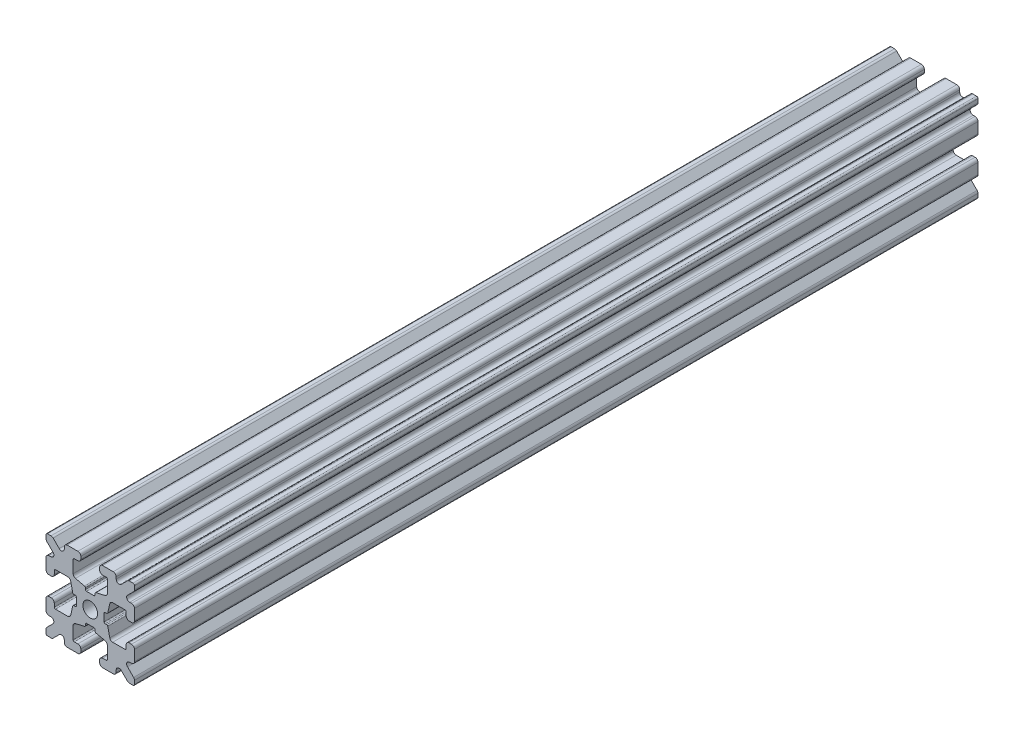
SolidWorks part; units mm, degrees
ref_plane "Front Plane" through (0, 0, 0) normal (0, 0, 1) x (1, 0, 0)
ref_plane "Top Plane" through (0, 0, 0) normal (0, 1, 0) x (1, 0, 0)
ref_plane "Right Plane" through (0, 0, 0) normal (1, 0, 0) x (0, 0, -1)
sketch "Sketch1" plane through (0, 0, 0) normal (0, 0, 1) x (1, 0, 0)
  line L1 (-7.5, -7.5) -> (7.5, -7.5)
  line L2 (-7.5, -7.5) -> (-7.5, 7.5)
  line L3 (-7.5, 7.5) -> (7.5, 7.5)
  line L4 (7.5, -7.5) -> (7.5, 7.5)
  line L5 (-7.5, -7.5) -> (7.5, 7.5) construction
  line L6 (-7.5, 7.5) -> (7.5, -7.5) construction
  circle A0 centre (0, 0) radius 1.25
  point P0 (0, 0)
  dimension "D2" = 2.5
  dimension "D1" = 15
extrude "Boss-Extrude1" add sketch "Sketch1" along normal mid plane 143
fillet "Fillet1" radius 0.25 4 edges at (7.5, -7.5, 0) (-7.5, -7.5, 0) (7.5, 7.5, 0) (-7.5, 7.5, 0)
sketch "Sketch2" plane through (0, 0, 71.5) normal (0, 0, 1) x (1, 0, 0)
  line L0 (-7.5, 7.25) -> (-7.5, -7.25) construction
  line L1 (-7.5, 1.6) -> (-6.1, 1.6)
  line L2 (-7.5, 1.6) -> (-7.5, -1.6)
  line L3 (-7.5, -1.6) -> (-6.1, -1.6)
  line L4 (-6.1, 1.6) -> (-6.1, 2.9)
  line L5 (0, 0) -> (-12.1036, 0) construction
  line L6 (-6.1, -2.9) -> (-3.4, -2.9)
  line L7 (0, 0) -> (-7.25, 7.25) construction
  line L8 (-6.1, 2.9) -> (-3.4, 2.9)
  line L9 (-3.4, -2.9) -> (-3.4, 2.9)
  line L10 (55, 0) -> (-55, 0) construction
  line L11 (-6.1, -2.9) -> (-6.1, -1.6)
  line L12 (2.9, 6.1) -> (1.6, 6.1)
  line L13 (2.9, 3.4) -> (-2.9, 3.4)
  line L14 (-2.9, 6.1) -> (-2.9, 3.4)
  line L15 (2.9, 6.1) -> (2.9, 3.4)
  line L16 (-1.6, 6.1) -> (-2.9, 6.1)
  line L17 (1.6, 7.5) -> (1.6, 6.1)
  line L18 (-1.6, 7.5) -> (1.6, 7.5)
  line L19 (-1.6, 7.5) -> (-1.6, 6.1)
  line L20 (-1.6, -7.5) -> (-1.6, -6.1)
  line L21 (-1.6, -7.5) -> (1.6, -7.5)
  line L22 (1.6, -7.5) -> (1.6, -6.1)
  line L23 (-1.6, -6.1) -> (-2.9, -6.1)
  line L24 (2.9, -6.1) -> (2.9, -3.4)
  line L25 (-2.9, -6.1) -> (-2.9, -3.4)
  line L26 (2.9, -3.4) -> (-2.9, -3.4)
  line L27 (2.9, -6.1) -> (1.6, -6.1)
  line L28 (6.1, -2.9) -> (6.1, -1.6)
  line L29 (3.4, -2.9) -> (3.4, 2.9)
  line L30 (6.1, 2.9) -> (3.4, 2.9)
  line L31 (6.1, -2.9) -> (3.4, -2.9)
  line L32 (6.1, 1.6) -> (6.1, 2.9)
  line L33 (7.5, -1.6) -> (6.1, -1.6)
  line L34 (7.5, 1.6) -> (7.5, -1.6)
  line L35 (7.5, 1.6) -> (6.1, 1.6)
  dimension "D1" = 3.2
  dimension "D2" = 5.8
  dimension "D3" = 1.4
  dimension "D4" = 2.7
extrude "Cut-Extrude1" cut sketch "Sketch2" against normal through all
sketch "Sketch4" plane through (0, 0, 71.5) normal (0, 0, 1) x (1, 0, 0)
  line L0 (-3.4, 2.9) -> (-2.75, 0)
  line L1 (55, 0) -> (-55, 0) construction
  line L2 (-2.75, 0) -> (-3.4, -2.9)
  line L3 (-3.4, -2.9) -> (-3.4, 2.9) construction
  line L4 (-3.4, 2.9) -> (-3.4, -2.9)
  line L5 (-2.9, 3.4) -> (0, 2.75)
  line L6 (0, 2.75) -> (2.9, 3.4)
  line L7 (2.9, 3.4) -> (-2.9, 3.4)
  line L8 (3.4, 2.9) -> (2.75, 0)
  line L9 (2.75, 0) -> (3.4, -2.9)
  line L10 (3.4, -2.9) -> (3.4, 2.9)
  line L11 (-2.9, -3.4) -> (0, -2.75)
  line L12 (0, -2.75) -> (2.9, -3.4)
  line L13 (2.9, -3.4) -> (-2.9, -3.4)
  circle A2 centre (0, 0) radius 2.75
  circle A3 centre (0, 0) radius 2.75 construction
  dimension "D1" = 1.5
extrude "Cut-Extrude3" cut sketch "Sketch4" against normal through all
fillet "Fillet3" radius 0.5 16 edges at (-6.1, -1.6, 0) (-7.5, -1.6, 0) (-6.1, 1.6, 0) (-7.5, 1.6, 0) (-1.6, -7.5, 0) (-1.6, -6.1, 0) (1.6, -7.5, 0) (1.6, -6.1, 0) (6.1, -1.6, 0) (7.5, -1.6, 0) (7.5, 1.6, 0) (6.1, 1.6, 0) (1.6, 7.5, 0) (1.6, 6.1, 0) (-1.6, 7.5, 0) (-1.6, 6.1, 0)
fillet "Fillet4" radius 0.5 8 edges at (-3.4, 2.9, 0) (-3.4, -2.9, 0) (2.9, -3.4, 0) (-2.9, -3.4, 0) (3.4, -2.9, 0) (3.4, 2.9, 0) (-2.9, 3.4, 0) (2.9, 3.4, 0)
fillet "Fillet5" radius 3 4 edges at (0, -2.75, 0) (2.75, 0, 0) (-2.75, 0, 0) (0, 2.75, 0)
fillet "Fillet6" radius 0.2 8 edges at (-2.9, -6.1, 0) (2.9, -6.1, 0) (6.1, -2.9, 0) (6.1, 2.9, 0) (2.9, 6.1, 0) (-2.9, 6.1, 0) (-6.1, -2.9, 0) (-6.1, 2.9, 0)
sketch "Sketch5" plane through (0, 0, 71.5) normal (0, 0, 1) x (1, 0, 0)
  line L0 (0, 0) -> (-7.25, 7.25) construction
  line L1 (-7.5, 6.4393) -> (-5.4607, 4.4)
  line L2 (-6.4393, 7.5) -> (-4.4, 5.4607)
  line L3 (-7.5, 4.4) -> (-5.4607, 4.4)
  line L4 (-3.8003, 2.9) -> (-5.9, 2.9) construction
  line L5 (0, 0) -> (-12.1819, 0) construction
  line L6 (-4.4, 7.5) -> (-4.4, 5.4607)
  line L7 (-2.9, 5.9) -> (-2.9, 3.8003) construction
  line L8 (-7.5, 6.4393) -> (-7.5, 4.4)
  line L9 (-7.5, 7.25) -> (-7.5, 2.1) construction
  line L10 (2.1, -7.5) -> (7.25, -7.5) construction
  line L11 (7.5, -7.25) -> (7.5, -2.1) construction
  line L12 (7.25, 7.5) -> (2.1, 7.5) construction
  line L13 (-2.1, 7.5) -> (-7.25, 7.5) construction
  line L14 (-4.4, 7.5) -> (-6.4393, 7.5)
  line L16 (55, 0) -> (-55, 0) construction
  line L17 (0, 0) -> (0, 10.993) construction
  line L18 (0, -54.6431) -> (0, 54.6431) construction
  line L20 (4.4, 7.5) -> (6.4393, 7.5)
  line L22 (7.5, 6.4393) -> (7.5, 4.4)
  line L23 (4.4, 7.5) -> (4.4, 5.4607)
  line L24 (7.5, 4.4) -> (5.4607, 4.4)
  line L25 (6.4393, 7.5) -> (4.4, 5.4607)
  line L26 (7.5, 6.4393) -> (5.4607, 4.4)
  line L27 (7.5, -6.4393) -> (5.4607, -4.4)
  line L28 (6.4393, -7.5) -> (4.4, -5.4607)
  line L29 (7.5, -4.4) -> (5.4607, -4.4)
  line L30 (4.4, -7.5) -> (4.4, -5.4607)
  line L31 (7.5, -6.4393) -> (7.5, -4.4)
  line L33 (4.4, -7.5) -> (6.4393, -7.5)
  line L36 (-4.4, -7.5) -> (-6.4393, -7.5)
  line L38 (-7.5, -6.4393) -> (-7.5, -4.4)
  line L39 (-4.4, -7.5) -> (-4.4, -5.4607)
  line L40 (-7.5, -4.4) -> (-5.4607, -4.4)
  line L41 (-6.4393, -7.5) -> (-4.4, -5.4607)
  line L42 (-7.5, -6.4393) -> (-5.4607, -4.4)
  dimension "D1" = 1.5
  dimension "D2" = 1.5
  dimension "D3" = 1.5
extrude "Cut-Extrude4" cut sketch "Sketch5" against normal through all
fillet "Fillet8" radius 0.5 24 edges at (-5.4607, 4.4, 0) (-7.5, 4.4, 0) (-5.4607, -4.4, 0) (-7.5, -4.4, 0) (-4.4, -7.5, 0) (-4.4, -5.4607, 0) (4.4, -7.5, 0) (4.4, -5.4607, 0) (5.4607, -4.4, 0) (7.5, -4.4, 0) (7.5, 4.4, 0) (5.4607, 4.4, 0) (4.4, 5.4607, 0) (4.4, 7.5, 0) (-4.4, 5.4607, 0) (-4.4, 7.5, 0) (-6.4393, 7.5, 0) (-7.5, 6.4393, 0) (6.4393, 7.5, 0) (7.5, 6.4393, 0) (6.4393, -7.5, 0) (7.5, -6.4393, 0) (-6.4393, -7.5, 0) (-7.5, -6.4393, 0)
sketch "Sketch6" plane through (0, 0, 71.5) normal (0, 0, 1) x (1, 0, 0)
  line L0 (0, 0) -> (0, 11.013) construction
  line L1 (0.6561, 2.8971) -> (2.1235, 2.8971) construction
  line L2 (0, -54.6431) -> (0, 54.6431) construction
  line L3 (0, 0) -> (7.25, 7.25) construction
  line L4 (7.5, 0.8255) -> (7.5, -0.8255)
  line L5 (2.3471, 0.8255) -> (7.5, 0.8255)
  line L6 (0, 0) -> (12.4016, 0) construction
  line L7 (0.8255, -7.5) -> (-0.8255, -7.5)
  line L8 (2.3471, -0.8255) -> (2.3471, 0.8255)
  line L9 (0.8255, -2.3471) -> (0.8255, -7.5)
  line L10 (7.5, -0.8255) -> (2.3471, -0.8255)
  line L11 (-7.5, -0.8255) -> (-2.3471, -0.8255)
  line L12 (-2.3471, -0.8255) -> (-2.3471, 0.8255)
  line L13 (-0.8255, -2.3471) -> (0.8255, -2.3471)
  line L14 (-0.8255, 7.5) -> (-0.8255, 2.3471)
  line L15 (-0.8255, 2.3471) -> (0.8255, 2.3471)
  line L16 (-0.8255, -7.5) -> (-0.8255, -2.3471)
  line L17 (0.8255, 2.3471) -> (0.8255, 7.5)
  line L18 (0.8255, 7.5) -> (-0.8255, 7.5)
  line L19 (3.9, 7.5) -> (2.1, 7.5) construction
  line L20 (-2.3471, 0.8255) -> (-7.5, 0.8255)
  line L21 (-7.5, 0.8255) -> (-7.5, -0.8255)
  point P5 (0, -2.5973)
  point P7 (0, 2.5973)
  dimension "D3" = 0.55
  dimension "D1" = 1.651
extrude "Cut-Extrude5" cut sketch "Sketch6" against normal through all
fillet "Fillet10" radius 0.2 16 edges at (-2.935, 0.8255, 0) (-2.935, -0.8255, 0) (2.935, -0.8255, 0) (2.935, 0.8255, 0) (0.8255, 2.935, 0) (-0.8255, 2.935, 0) (-2.3471, 0.8255, 0) (-2.3471, -0.8255, 0) (0.8255, 2.3471, 0) (-0.8255, 2.3471, 0) (2.3471, 0.8255, 0) (2.3471, -0.8255, 0) (0.8255, -2.935, 0) (0.8255, -2.3471, 0) (-0.8255, -2.3471, 0) (-0.8255, -2.935, 0)
